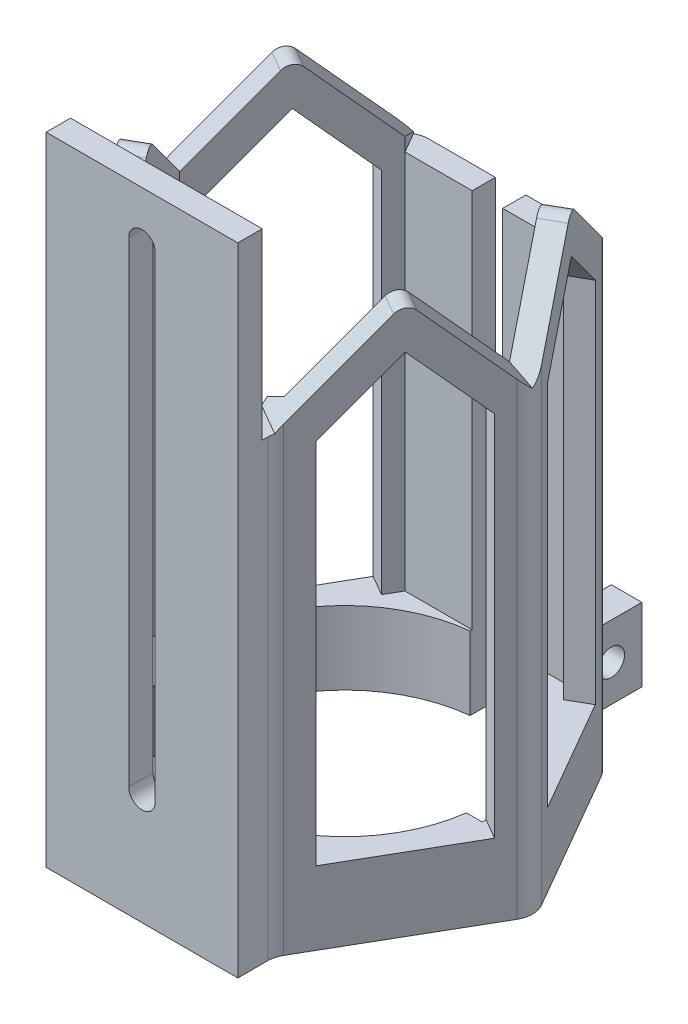
SolidWorks part; units mm, degrees
ref_plane "Front Plane" through (0, 0, 0) normal (0, 0, 1) x (1, 0, 0)
ref_plane "Top Plane" through (0, 0, 0) normal (0, 1, 0) x (1, 0, 0)
ref_plane "Right Plane" through (0, 0, 0) normal (1, 0, 0) x (0, 0, -1)
sketch "Sketch1" plane through (0, 0, 0) normal (0, 1, 0) x (1, 0, 0)
  line L1 (39.8834, 0) -> (19.9417, 34.54)
  line L2 (19.9417, 34.54) -> (9.525, 34.54)
  line L3 (-19.9417, 34.54) -> (-39.8834, 0)
  line L4 (-39.8834, 0) -> (-19.9417, -34.54)
  line L5 (-19.9417, -34.54) -> (19.9417, -34.54)
  line L6 (19.9417, -34.54) -> (39.8834, 0)
  line L7 (0, -55) -> (0, 55) construction
  line L8 (-3.175, 34.54) -> (-3.175, 52.32)
  line L9 (-3.175, 52.32) -> (-9.525, 52.32)
  line L10 (-9.525, 52.32) -> (-9.525, 34.54)
  line L11 (3.175, 52.32) -> (9.525, 52.32)
  line L12 (9.525, 52.32) -> (9.525, 34.54)
  line L13 (3.175, 34.54) -> (3.175, 52.32)
  line L14 (-3.175, 34.54) -> (-3.175, 29.2884)
  line L15 (3.175, 34.54) -> (3.175, 29.2884)
  line L17 (-9.525, 34.54) -> (-19.9417, 34.54)
  arc A0 (-3.175, 29.2884) -> (3.175, 29.2884) centre (0, 0) ccw
  circle A1 centre (0, 0) radius 34.54 construction
  dimension "D1" = 58.92
  dimension "D3" = 5.08
  dimension "D4" = 6.35
  dimension "D5" = 6.35
  dimension "D6" = 17.78
extrude "Boss-Extrude1" add sketch "Sketch1" along normal blind 114.3
sketch "Sketch2" plane through (0, 114.3, 0) normal (0, 1, 0) x (1, 0, 0)
  line L0 (0, -51.964) -> (0, 51.964) construction
  line L1 (-9.525, 34.54) -> (-3.175, 34.54)
  line L2 (-9.525, 34.54) -> (-9.525, 52.32)
  line L3 (-9.525, 52.32) -> (-3.175, 52.32)
  line L4 (-3.175, 34.54) -> (-3.175, 52.32)
  line L5 (9.525, 52.32) -> (3.175, 52.32)
  line L6 (3.175, 34.54) -> (3.175, 52.32)
  line L7 (9.525, 34.54) -> (3.175, 34.54)
  line L8 (9.525, 34.54) -> (9.525, 52.32)
extrude "Cut-Extrude2" cut sketch "Sketch2" against normal blind 99.06
sketch "Sketch3" plane through (-29.9125, 0, -17.27) normal (-0.866, 0, -0.5) x (-0.5, 0, 0.866)
  line L0 (-19.9417, 57.15) -> (19.9417, 57.15) construction
  line L1 (-19.9417, 114.3) -> (-19.9417, 0) construction
  line L2 (19.9417, 114.3) -> (19.9417, 0) construction
  line L3 (-19.9417, 114.3) -> (19.9417, 114.3) construction
  line L4 (-13.5917, 15.24) -> (13.5917, 15.24)
  line L5 (-13.5917, 15.24) -> (-13.5917, 99.06)
  line L6 (-13.5917, 99.06) -> (13.5917, 99.06)
  line L7 (13.5917, 15.24) -> (13.5917, 99.06)
  line L10 (-13.5917, 15.24) -> (13.5917, 99.06) construction
  line L16 (-13.5917, 99.06) -> (13.5917, 15.24) construction
  point P6 (0, 57.15)
  dimension "D1" = 15.24
  dimension "D2" = 6.35
extrude "Cut-Extrude3" cut sketch "Sketch3" against normal blind 99.06
sketch "Sketch4" plane through (29.9125, 0, -17.27) normal (0.866, 0, -0.5) x (-0.5, 0, -0.866)
  line L4 (-19.9417, 57.15) -> (19.9417, 57.15) construction
  line L5 (-19.9417, 114.3) -> (-19.9417, 0) construction
  line L6 (19.9417, 114.3) -> (19.9417, 0) construction
  line L7 (-19.9417, 114.3) -> (19.9417, 114.3) construction
  line L8 (-13.5917, 15.24) -> (13.5917, 15.24)
  line L9 (-13.5917, 15.24) -> (-13.5917, 99.06)
  line L10 (-13.5917, 99.06) -> (13.5917, 99.06)
  line L11 (13.5917, 15.24) -> (13.5917, 99.06)
  line L16 (-13.5917, 15.24) -> (13.5917, 99.06) construction
  line L17 (-13.5917, 99.06) -> (13.5917, 15.24) construction
  point P6 (0, 57.15)
  dimension "D1" = 15.24
  dimension "D2" = 6.35
extrude "Cut-Extrude4" cut sketch "Sketch4" against normal blind 99.06
sketch "Sketch7" plane through (0, 0, 0) normal (0, -1, 0) x (1, 0, 0)
  line L0 (43.4395, 0) -> (-43.4395, 0) construction
  line L1 (-32.47, -3.8568) -> (-29.2064, -3.8568)
  line L2 (-32.47, -3.8568) -> (-32.47, 3.8568)
  line L3 (-32.47, 3.8568) -> (-29.2064, 3.8568)
  line L4 (-29.2064, -3.8568) -> (-29.2064, 3.8568)
  line L5 (-32.47, -3.8568) -> (-29.2064, 3.8568) construction
  line L6 (-32.47, 3.8568) -> (-29.2064, -3.8568) construction
  line L7 (0, -51.964) -> (0, 51.964) construction
  line L8 (32.47, 3.8568) -> (29.2064, 3.8568)
  line L9 (29.2064, -3.8568) -> (29.2064, 3.8568)
  line L10 (32.47, -3.8568) -> (29.2064, -3.8568)
  line L11 (32.47, -3.8568) -> (32.47, 3.8568)
  arc A0 (3.175, -29.2884) -> (-3.175, -29.2884) centre (0, 0) ccw construction
  point P0 (-30.8382, 0)
  dimension "D1" = 3.2635
  dimension "D2" = 7.7136
extrude "Cut-Extrude7" cut sketch "Sketch7" against normal blind 15.24
sketch "Sketch8" plane through (0, 114.3, 0) normal (0, 1, 0) x (1, 0, 0)
  line L28 (-3.175, 29.714) -> (3.175, 29.714)
  line L35 (-34.3108, 0) -> (-17.1554, -29.714)
  line L36 (-17.1554, -29.714) -> (17.1554, -29.714)
  line L37 (17.1554, -29.714) -> (34.3108, 0)
  line L38 (34.3108, 0) -> (17.1554, 29.714)
  line L39 (17.1554, 29.714) -> (3.175, 29.714)
  line L40 (-17.1554, 29.714) -> (-34.3108, 0)
  line L41 (-3.175, 29.714) -> (-17.1554, 29.714)
  line L42 (-34.3108, 0) -> (-17.1554, -29.714)
  line L43 (-17.1554, -29.714) -> (17.1554, -29.714)
  line L44 (17.1554, -29.714) -> (34.3108, 0)
  line L45 (34.3108, 0) -> (17.1554, 29.714)
  line L46 (17.1554, 29.714) -> (3.175, 29.714)
  line L47 (-17.1554, 29.714) -> (-34.3108, 0)
  line L48 (-3.175, 29.714) -> (-17.1554, 29.714)
  dimension "D1" = 4.826
extrude "Cut-Extrude8" cut sketch "Sketch8" against normal blind 99.06
sketch "Sketch10" plane through (0, 0, 34.54) normal (0, 0, 1) x (1, 0, 0)
  line L0 (43.4395, 0) -> (-43.4395, 0) construction
  line L1 (-19.9417, 114.3) -> (19.9417, 114.3)
  line L2 (-19.9417, 114.3) -> (-19.9417, 0)
  line L3 (-19.9417, 0) -> (19.9417, 0)
  line L4 (19.9417, 114.3) -> (19.9417, 0)
  line L5 (19.9417, 114.3) -> (19.9417, 0) construction
extrude "Boss-Extrude2" add sketch "Sketch10" along normal blind 7.62
sketch "Sketch11" plane through (-29.9125, 0, -17.27) normal (-0.866, 0, -0.5) x (-0.5, 0, 0.866)
  line L0 (-13.5917, 91.7281) -> (0, 105.3197)
  line L1 (0, 0) -> (0, 114.3) construction
  line L2 (-19.9417, 94.3583) -> (0, 114.3)
  line L3 (-19.9417, 114.3) -> (-19.9417, 0) construction
  line L4 (-19.9417, 114.3) -> (19.9417, 114.3) construction
  line L7 (-13.5917, 99.06) -> (-13.5917, 15.24) construction
  line L8 (-13.5917, 91.7281) -> (0, 91.7281) construction
  line L9 (19.9417, 94.3583) -> (0, 114.3)
  line L10 (13.5917, 91.7281) -> (0, 105.3197)
  line L11 (-19.9417, 94.3583) -> (-13.5917, 91.7281)
  line L12 (13.5917, 91.7281) -> (19.9417, 94.3583)
  dimension "D1" = 6.35
  dimension "D2" = 45
sketch "Sketch12" plane through (-29.9125, 0, -17.27) normal (-0.866, 0, -0.5) x (-0.5, 0, 0.866)
  line L0 (0, 114.3) -> (-19.9417, 94.3583)
  line L1 (-19.9417, 94.3583) -> (-19.9417, 114.3)
  line L2 (-19.9417, 114.3) -> (0, 114.3)
  line L3 (0, 114.3) -> (19.9417, 114.3)
  line L4 (19.9417, 114.3) -> (19.9417, 94.3583)
  line L5 (19.9417, 94.3583) -> (0, 114.3)
  line L6 (0, 105.3197) -> (-6.2597, 99.06)
  line L7 (13.5917, 99.06) -> (-13.5917, 99.06) construction
  line L8 (-6.2597, 99.06) -> (6.2597, 99.06)
  line L9 (6.2597, 99.06) -> (0, 105.3197)
  line L10 (13.5917, 91.7281) -> (0, 105.3197) construction
  line M4 (-13.5917, 99.06) -> (13.5917, 99.06)
  line M9 (19.9417, 0) -> (19.9417, 114.3)
  line M10 (19.9417, 114.3) -> (-19.9417, 114.3)
  line M11 (-19.9417, 114.3) -> (-19.9417, 0)
extrude "Cut-Extrude11" cut sketch "Sketch12" against normal blind 81.28 contours L5 M9 M10 | L0 M10 M11 | L9 L6 M4
mirror "Mirror2" about plane through (0, 0, 0) normal (1, 0, 0) of "Cut-Extrude11"
sketch "Sketch14" plane through (0, 0, -34.54) normal (0, 0, -1) x (-1, 0, 0)
  line L0 (-19.9417, 94.3583) -> (19.9417, 94.3583)
  line L1 (19.9417, 94.3583) -> (19.9417, 114.3)
  line L2 (19.9417, 114.3) -> (-19.9417, 114.3)
  line L3 (-19.9417, 114.3) -> (-19.9417, 94.3583)
extrude "Boss-Extrude9" add sketch "Sketch11" against normal blind 4.826
mirror "Mirror8" about plane through (0, 0, 0) normal (0, 0, 1) of "Boss-Extrude9"
mirror "Mirror9" about plane through (0, 0, 0) normal (1, 0, 0) of "Mirror8", "Boss-Extrude9"
sketch "Sketch15" plane through (0, 114.3, 0) normal (0, 1, 0) x (1, 0, 0)
  line L0 (-17.1554, 29.714) -> (-19.9417, 34.54)
  line L1 (-19.9417, 34.54) -> (19.9417, 34.54)
  line L2 (19.9417, 34.54) -> (17.1554, 29.714)
  line L3 (17.1554, 29.714) -> (-17.1554, 29.714)
extrude "Cut-Extrude13" cut sketch "Sketch15" against normal blind 19.9417
sketch "Sketch16" plane through (0, 114.3, 0) normal (0, 1, 0) x (1, 0, 0)
  line L0 (-19.9417, -34.54) -> (19.9417, -34.54)
  line L1 (19.9417, -34.54) -> (11.5828, -29.714)
  line L2 (11.5828, -29.714) -> (-11.5828, -29.714)
  line L3 (-11.5828, -29.714) -> (-19.9417, -34.54)
extrude "Cut-Extrude14" cut sketch "Sketch16" against normal blind 19.9417
sketch "Sketch17" plane through (0, 114.3, 0) normal (0, 1, 0) x (1, 0, 0)
  line L0 (0, -29.714) -> (0, -34.54) construction
  line L1 (11.5828, -29.714) -> (-11.5828, -29.714) construction
  line L2 (0, -51.964) -> (0, 51.964) construction
  line L3 (-19.9417, -34.54) -> (19.9417, -34.54) construction
  line L4 (-17.1554, -29.714) -> (17.1554, -29.714) construction
  line L5 (-13.5917, -34.54) -> (13.5917, -34.54)
  line L6 (-13.5917, -34.54) -> (-13.5917, -29.714)
  line L7 (-13.5917, -29.714) -> (13.5917, -29.714)
  line L8 (13.5917, -34.54) -> (13.5917, -29.714)
  line L9 (-13.5917, -34.54) -> (13.5917, -29.714) construction
  line L10 (-13.5917, -29.714) -> (13.5917, -34.54) construction
  point P10 (0, -32.127)
  dimension "D1" = 3.5637
extrude "Cut-Extrude15" cut sketch "Sketch17" against normal blind 99.06
sketch "Sketch18" plane through (0, 114.3, 0) normal (0, 1, 0) x (1, 0, 0)
  line L0 (19.9417, -34.54) -> (13.5917, -30.8738) construction
  line L1 (-19.9417, -42.16) -> (19.9417, -42.16)
  line L2 (-19.9417, -42.16) -> (-19.9417, -34.54)
  line L3 (-19.9417, -34.54) -> (19.9417, -34.54)
  line L4 (19.9417, -42.16) -> (19.9417, -34.54)
  line L5 (13.5917, -34.54) -> (19.9417, -34.54) construction
extrude "Cut-Extrude16" cut sketch "Sketch18" against normal blind 19.9417
sketch "Sketch20" plane through (0, 94.3583, 0) normal (0, 1, 0) x (1, 0, 0)
  line L0 (-13.5917, -34.54) -> (-13.5917, -37.08)
  line L1 (-13.5917, -37.08) -> (13.5917, -37.08)
  line L2 (13.5917, -34.54) -> (13.5917, -37.08)
  line L3 (-13.5917, -34.54) -> (13.5917, -34.54)
  line L4 (-19.9417, -42.16) -> (19.9417, -42.16) construction
  dimension "D1" = 5.08
extrude "Cut-Extrude19" cut sketch "Sketch20" against normal blind 79.1183
fillet "Fillet1" radius 5.08 8 edges at (19.9417, 47.1792, 34.54) (-19.9417, 47.1792, 34.54) (39.8834, 47.1792, 0) (19.9417, 47.1792, -34.54) (9.525, 7.62, -34.54) (-9.525, 7.62, -34.54) (-39.8834, 47.1792, 0) (-19.9417, 47.1792, -34.54)
fillet "Fillet2" radius 2.54 4 edges at (27.8228, 114.3, 16.0635) (-27.8228, 114.3, -16.0635) (-27.8228, 114.3, 16.0635) (27.8228, 114.3, -16.0635)
sketch "Sketch21" plane through (9.525, 0, 0) normal (1, 0, 0) x (0, 0, -1)
  line L0 (45.97, 15.24) -> (45.97, 0) construction
  line L1 (39.62, 15.24) -> (52.32, 15.24) construction
  line L2 (43.4395, 0) -> (-43.4395, 0) construction
  circle A0 centre (45.97, 7.62) radius 2.75
  circle A1 centre (45.97, 7.62) radius 4.75 construction
  dimension "D1" = 5.5
  dimension "D2" = 9.5
extrude "Cut-Extrude20" cut sketch "Sketch21" against normal blind 79.1183
sketch "Sketch22" plane through (0, 94.3583, 0) normal (0, 1, 0) x (1, 0, 0)
  line L0 (19.9417, -42.16) -> (19.9417, -35.9012) construction
  line L1 (-19.9417, -42.16) -> (19.9417, -42.16)
  line L2 (-19.9417, -42.16) -> (-19.9417, -37.08)
  line L3 (-19.9417, -37.08) -> (19.9417, -37.08)
  line L4 (19.9417, -42.16) -> (19.9417, -37.08)
  line L5 (-13.5917, -37.08) -> (13.5917, -37.08) construction
extrude "Boss-Extrude10" add sketch "Sketch22" along normal blind 38.1
sketch "Sketch23" plane through (0, 0, 42.16) normal (0, 0, 1) x (1, 0, 0)
  line L0 (0, 122.13) -> (0, 23.07) construction
  line L1 (0, -51.964) -> (0, 51.964) construction
  line L2 (2.75, 122.13) -> (2.75, 23.07)
  line L3 (-2.75, 122.13) -> (-2.75, 23.07)
  line L4 (43.4395, 0) -> (-43.4395, 0) construction
  arc A0 (2.75, 122.13) -> (-2.75, 122.13) centre (0, 122.13) ccw
  arc A1 (-2.75, 23.07) -> (2.75, 23.07) centre (0, 23.07) ccw
  point P5 (0, 72.6)
  point P10 (0, 20.32)
  dimension "D2" = 99.06
  dimension "D3" = 20.32
  dimension "D1" = 5.5
extrude "Cut-Extrude21" cut sketch "Sketch23" against normal up to next contours L2 A1 L3 A0
ref_plane "Plane1" through (0, 0, 0) normal (-0.866, 0, 0.5) x (0.5, 0, 0.866)
